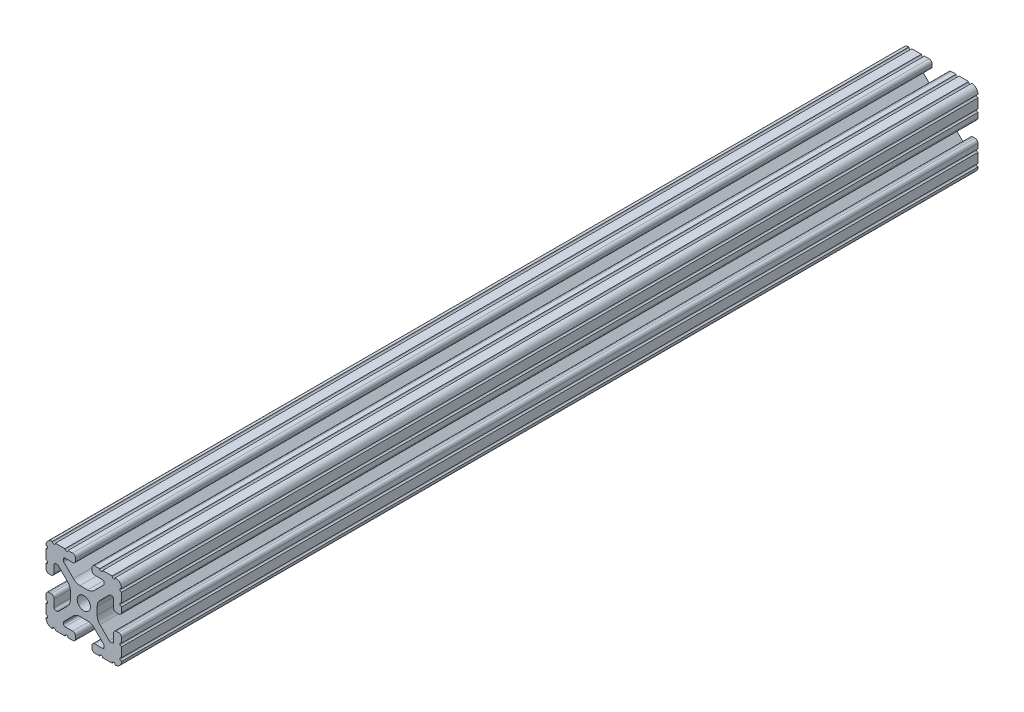
SolidWorks part; units mm, degrees
material "6061 Alloy"
ref_plane "Front Plane" through (0, 0, 0) normal (0, 0, 1) x (1, 0, 0)
ref_plane "Top Plane" through (0, 0, 0) normal (0, 1, 0) x (1, 0, 0)
ref_plane "Right Plane" through (0, 0, 0) normal (1, 0, 0) x (0, 0, -1)
sketch "Sketch1" plane through (0, 0, 0) normal (0, 0, 1) x (1, 0, 0)
  line L0 (0, 25.6181) -> (0, -24.623) construction
  line L1 (-20.8943, 0) -> (20.4607, 0) construction
  line L2 (-10.0229, 12.9148) -> (-5.2522, 8.144)
  line L3 (-10.287, 14.0843) -> (-10.287, 13.5524)
  line L4 (-5.6176, 14.986) -> (-9.3853, 14.986)
  line L5 (-4.064, 17.4964) -> (-4.064, 16.5396)
  line L6 (-7.9742, 19.05) -> (-5.6176, 19.05)
  line L7 (-14.3277, 19.05) -> (-9.4982, 19.05)
  line L8 (-19.05, 9.4961) -> (-19.05, 14.3277)
  line L9 (-19.05, 5.6176) -> (-19.05, 7.9763)
  line L10 (-16.5396, 4.064) -> (-17.4964, 4.064)
  line L11 (-14.986, 9.3853) -> (-14.986, 5.6176)
  line L12 (-13.516, 10.287) -> (-14.0843, 10.287)
  line L13 (-8.1476, 5.2921) -> (-12.8784, 10.0229)
  line L14 (-6.7564, -1.9335) -> (-6.7564, 1.9335)
  line L15 (-12.8784, -10.0229) -> (-8.1476, -5.2921)
  line L16 (-14.0843, -10.287) -> (-13.516, -10.287)
  line L17 (-14.986, -5.6176) -> (-14.986, -9.3853)
  line L18 (-17.4964, -4.064) -> (-16.5396, -4.064)
  line L19 (-19.05, -7.9763) -> (-19.05, -5.6176)
  line L20 (-19.05, -14.3277) -> (-19.05, -9.4961)
  line L21 (-9.4961, -19.05) -> (-14.3277, -19.05)
  line L22 (-5.6176, -19.05) -> (-7.9763, -19.05)
  line L23 (-4.064, -17.4964) -> (-4.064, -16.5396)
  line L24 (10.0229, -12.9148) -> (5.2522, -8.144)
  line L25 (10.287, -14.0843) -> (10.287, -13.5524)
  line L26 (5.6176, -14.986) -> (9.3853, -14.986)
  line L28 (-1.9022, 6.7564) -> (1.9022, 6.7564)
  line L29 (-1.9022, -6.7564) -> (1.9022, -6.7564)
  line L31 (-5.6176, -14.986) -> (-9.3853, -14.986)
  line L32 (-10.287, -14.0843) -> (-10.287, -13.5524)
  line L33 (-10.0229, -12.9148) -> (-5.2522, -8.144)
  line L66 (4.064, -16.5396) -> (4.064, -17.4964)
  line L67 (5.6176, -19.05) -> (7.9763, -19.05)
  line L68 (9.4961, -19.05) -> (14.3277, -19.05)
  line L69 (19.05, -14.3277) -> (19.05, -9.4961)
  line L70 (19.05, -7.9763) -> (19.05, -5.6176)
  line L71 (17.4964, -4.064) -> (16.5396, -4.064)
  line L72 (14.986, -5.6176) -> (14.986, -9.3853)
  line L73 (14.0843, -10.287) -> (13.516, -10.287)
  line L74 (12.8784, -10.0229) -> (8.1476, -5.2921)
  line L75 (6.7564, -1.9335) -> (6.7564, 1.9335)
  line L76 (8.1476, 5.2921) -> (12.8784, 10.0229)
  line L77 (13.516, 10.287) -> (14.0843, 10.287)
  line L78 (14.986, 9.3853) -> (14.986, 5.6176)
  line L79 (16.5396, 4.064) -> (17.4964, 4.064)
  line L80 (19.05, 5.6176) -> (19.05, 7.9763)
  line L81 (19.05, 9.4961) -> (19.05, 14.3277)
  line L82 (14.3277, 19.05) -> (9.4982, 19.05)
  line L83 (7.9742, 19.05) -> (5.6176, 19.05)
  line L84 (4.064, 17.4964) -> (4.064, 16.5396)
  line L85 (5.6176, 14.986) -> (9.3853, 14.986)
  line L86 (10.287, 14.0843) -> (10.287, 13.5524)
  line L87 (10.0229, 12.9148) -> (5.2522, 8.144)
  arc A0 (-10.0229, 12.9148) -> (-10.287, 13.5524) centre (-9.3853, 13.5524) cw
  circle A1 centre (0, 0) radius 3.3274
  arc A2 (-10.287, 14.0843) -> (-9.3853, 14.986) centre (-9.3853, 14.0843) cw
  arc A3 (-4.064, 16.5396) -> (-5.6176, 14.986) centre (-5.6176, 16.5396) cw
  arc A4 (-5.6176, 19.05) -> (-4.064, 17.4964) centre (-5.6176, 17.4964) cw
  arc A5 (-7.9742, 19.05) -> (-9.4982, 19.05) centre (-8.7362, 19.05) cw
  arc A6 (-14.3277, 19.05) -> (-15.8475, 19.05) centre (-15.0876, 18.9933) cw
  arc A7 (-19.05, 15.8475) -> (-15.8475, 19.05) centre (-15.8751, 15.8751) cw
  arc A8 (-19.05, 15.8475) -> (-19.05, 14.3277) centre (-18.9933, 15.0876) cw
  arc A9 (-19.05, 9.4961) -> (-19.05, 7.9763) centre (-18.9933, 8.7362) cw
  arc A10 (-17.4964, 4.064) -> (-19.05, 5.6176) centre (-17.4964, 5.6176) cw
  arc A11 (-14.986, 5.6176) -> (-16.5396, 4.064) centre (-16.5396, 5.6176) cw
  arc A12 (-14.986, 9.3853) -> (-14.0843, 10.287) centre (-14.0843, 9.3853) cw
  arc A13 (-13.516, 10.287) -> (-12.8784, 10.0229) centre (-13.516, 9.3853) cw
  arc A14 (-8.1476, 5.2921) -> (-6.7564, 1.9335) centre (-11.5062, 1.9335) cw
  arc A15 (-6.7564, -1.9335) -> (-8.1476, -5.2921) centre (-11.5062, -1.9335) cw
  arc A16 (-12.8784, -10.0229) -> (-13.516, -10.287) centre (-13.516, -9.3853) cw
  arc A17 (-14.0843, -10.287) -> (-14.986, -9.3853) centre (-14.0843, -9.3853) cw
  arc A18 (-16.5396, -4.064) -> (-14.986, -5.6176) centre (-16.5396, -5.6176) cw
  arc A19 (-19.05, -5.6176) -> (-17.4964, -4.064) centre (-17.4964, -5.6176) cw
  arc A20 (-19.05, -7.9763) -> (-19.05, -9.4961) centre (-18.9933, -8.7362) cw
  arc A21 (-19.05, -14.3277) -> (-19.05, -15.8475) centre (-18.9933, -15.0876) cw
  arc A22 (-15.8475, -19.05) -> (-19.05, -15.8475) centre (-15.8751, -15.8751) cw
  arc A23 (-15.8475, -19.05) -> (-14.3277, -19.05) centre (-15.0876, -18.9933) cw
  arc A24 (-9.4961, -19.05) -> (-7.9763, -19.05) centre (-8.7362, -18.9933) cw
  arc A25 (-4.064, -17.4964) -> (-5.6176, -19.05) centre (-5.6176, -17.4964) cw
  arc A26 (-5.2522, -8.144) -> (-1.9022, -6.7564) centre (-1.9022, -11.494) cw
  arc A27 (1.9022, -6.7564) -> (5.2522, -8.144) centre (1.9022, -11.494) cw
  arc A28 (10.0229, -12.9148) -> (10.287, -13.5524) centre (9.3853, -13.5524) cw
  arc A29 (10.287, -14.0843) -> (9.3853, -14.986) centre (9.3853, -14.0843) cw
  arc A30 (4.064, -16.5396) -> (5.6176, -14.986) centre (5.6176, -16.5396) cw
  arc A31 (-4.064, -16.5396) -> (-5.6176, -14.986) centre (-5.6176, -16.5396) ccw
  arc A32 (-10.287, -14.0843) -> (-9.3853, -14.986) centre (-9.3853, -14.0843) ccw
  arc A33 (-10.0229, -12.9148) -> (-10.287, -13.5524) centre (-9.3853, -13.5524) ccw
  arc A79 (4.064, -17.4964) -> (5.6176, -19.05) centre (5.6176, -17.4964) ccw
  arc A80 (9.4961, -19.05) -> (7.9763, -19.05) centre (8.7362, -18.9933) ccw
  arc A81 (15.8475, -19.05) -> (14.3277, -19.05) centre (15.0876, -18.9933) ccw
  arc A82 (15.8475, -19.05) -> (19.05, -15.8475) centre (15.8751, -15.8751) ccw
  arc A83 (19.05, -14.3277) -> (19.05, -15.8475) centre (18.9933, -15.0876) ccw
  arc A84 (19.05, -7.9763) -> (19.05, -9.4961) centre (18.9933, -8.7362) ccw
  arc A85 (19.05, -5.6176) -> (17.4964, -4.064) centre (17.4964, -5.6176) ccw
  arc A86 (16.5396, -4.064) -> (14.986, -5.6176) centre (16.5396, -5.6176) ccw
  arc A87 (14.0843, -10.287) -> (14.986, -9.3853) centre (14.0843, -9.3853) ccw
  arc A88 (12.8784, -10.0229) -> (13.516, -10.287) centre (13.516, -9.3853) ccw
  arc A89 (6.7564, -1.9335) -> (8.1476, -5.2921) centre (11.5062, -1.9335) ccw
  arc A90 (8.1476, 5.2921) -> (6.7564, 1.9335) centre (11.5062, 1.9335) ccw
  arc A91 (13.516, 10.287) -> (12.8784, 10.0229) centre (13.516, 9.3853) ccw
  arc A92 (14.986, 9.3853) -> (14.0843, 10.287) centre (14.0843, 9.3853) ccw
  arc A93 (14.986, 5.6176) -> (16.5396, 4.064) centre (16.5396, 5.6176) ccw
  arc A94 (17.4964, 4.064) -> (19.05, 5.6176) centre (17.4964, 5.6176) ccw
  arc A95 (19.05, 9.4961) -> (19.05, 7.9763) centre (18.9933, 8.7362) ccw
  arc A96 (19.05, 15.8475) -> (19.05, 14.3277) centre (18.9933, 15.0876) ccw
  arc A97 (19.05, 15.8475) -> (15.8475, 19.05) centre (15.8751, 15.8751) ccw
  arc A98 (14.3277, 19.05) -> (15.8475, 19.05) centre (15.0876, 18.9933) ccw
  arc A99 (7.9742, 19.05) -> (9.4982, 19.05) centre (8.7362, 19.05) ccw
  arc A100 (5.6176, 19.05) -> (4.064, 17.4964) centre (5.6176, 17.4964) ccw
  arc A101 (4.064, 16.5396) -> (5.6176, 14.986) centre (5.6176, 16.5396) ccw
  arc A102 (10.287, 14.0843) -> (9.3853, 14.986) centre (9.3853, 14.0843) ccw
  arc A103 (10.0229, 12.9148) -> (10.287, 13.5524) centre (9.3853, 13.5524) ccw
  arc A104 (1.9022, 6.7564) -> (5.2522, 8.144) centre (1.9022, 11.494) ccw
  arc A105 (-5.2522, 8.144) -> (-1.9022, 6.7564) centre (-1.9022, 11.494) ccw
  dimension "D1" = 6.6548
  dimension "D2" = 19.05
  dimension "D3" = 38.1
  dimension "D4" = 20.574
  dimension "D5" = 13.5128
  dimension "D6" = 4.064
  dimension "D7" = 8.128
  dimension "D8" = 4.064
  dimension "D9" = 12.2936
extrude "Extrude1" add sketch "Sketch1" against normal blind 431.8
